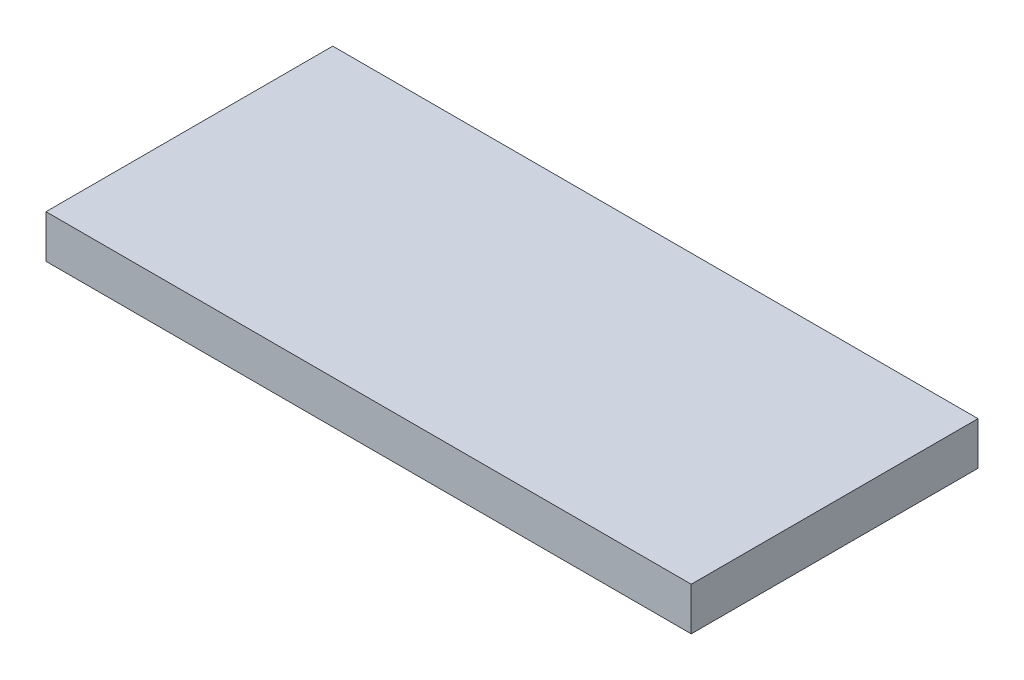
SolidWorks part; units mm, degrees
ref_plane "Front Plane" through (0, 0, 0) normal (0, 0, 1) x (1, 0, 0)
ref_plane "Top Plane" through (0, 0, 0) normal (0, 1, 0) x (1, 0, 0)
ref_plane "Right Plane" through (0, 0, 0) normal (1, 0, 0) x (0, 0, -1)
sketch "Sketch1" plane through (0, 0, 0) normal (0, 1, 0) x (1, 0, 0)
  line L1 (-22.5, -10) -> (22.5, -10)
  line L2 (-22.5, -10) -> (-22.5, 10)
  line L3 (-22.5, 10) -> (22.5, 10)
  line L4 (22.5, -10) -> (22.5, 10)
  line L5 (-22.5, -10) -> (22.5, 10) construction
  line L6 (-22.5, 10) -> (22.5, -10) construction
  point P0 (0, 0)
  dimension "D1" = 45
  dimension "D2" = 20
extrude "Boss-Extrude1" add sketch "Sketch1" along normal blind 3
sketch "Sketch2" plane through (0, 0, 0) normal (0, -1, 0) x (1, 0, 0)
  line L1 (-19.5, -4.7) -> (19.5, -4.7)
  line L2 (-19.5, -4.7) -> (-19.5, 4.7)
  line L3 (-19.5, 4.7) -> (19.5, 4.7)
  line L4 (19.5, -4.7) -> (19.5, 4.7)
  line L5 (-19.5, -4.7) -> (19.5, 4.7) construction
  line L6 (-19.5, 4.7) -> (19.5, -4.7) construction
  line L7 (-22.5, -10) -> (-22.5, 10) construction
  point P0 (0, 0)
  point P8 (0, 0)
  dimension "D1" = 9.4
  dimension "D2" = 3
extrude "Cut-Extrude1" cut sketch "Sketch2" against normal blind 1.5
